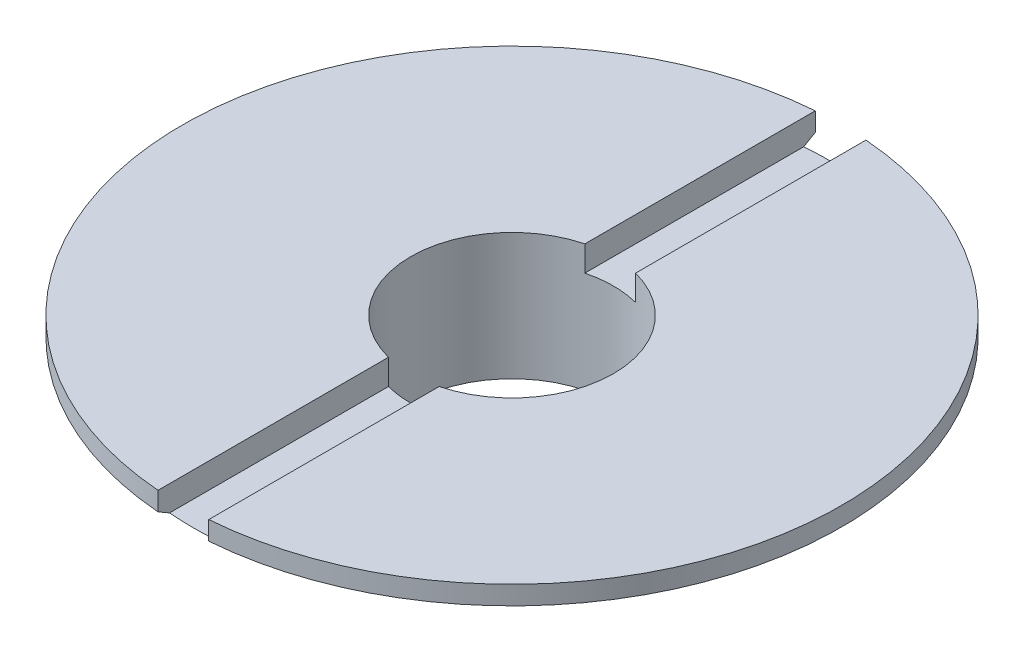
SolidWorks part; units mm, degrees
ref_plane "Front Plane" through (0, 0, 0) normal (0, 0, 1) x (1, 0, 0)
ref_plane "Top Plane" through (0, 0, 0) normal (0, 1, 0) x (1, 0, 0)
ref_plane "Right Plane" through (0, 0, 0) normal (1, 0, 0) x (0, 0, -1)
sketch "Sketch1" plane through (0, 0, 0) normal (1, 0, 0) x (0, 0, -1)
  line L0 (0, 36.0981) -> (0, -28.6608) construction
  line L1 (-13, 1.7612) -> (-5.6194, -2.5)
  line L2 (-5.6194, -2.5) -> (-4, -2.5)
  line L3 (-13, 2.5) -> (-4, 2.5)
  line L4 (-4, 2.5) -> (-4, -2.5)
  line L5 (-4, 2.5) -> (0, 2.5) construction
  line L6 (-4, -2.5) -> (0, -2.5) construction
  line L7 (-13, 2.5) -> (-13, 1.7612)
  line L8 (-14.2796, 2.5) -> (-13, 2.5) construction
  line L9 (-14.2796, 2.5) -> (-13, 1.7612) construction
  point P10 (-4, 0)
  point P11 (-4.9408, -0.7388)
  point P13 (-13, 0)
  dimension "D1" = 30
  dimension "D2" = 5
  dimension "D3" = 8
  dimension "D5" = 26
revolve "Revolve1" add sketch "Sketch1" angle 360 about L0
sketch "Sketch2" plane through (0, 2.5, 0) normal (0, 1, 0) x (1, 0, 0)
  line L0 (0, 13) -> (0, -13)
  circle A0 centre (0, 0) radius 13 construction
extrude "Cut-Extrude-Thin2" cut sketch "Sketch2" against normal blind 1 and the other way through all thin thin type mid plane wall 2
